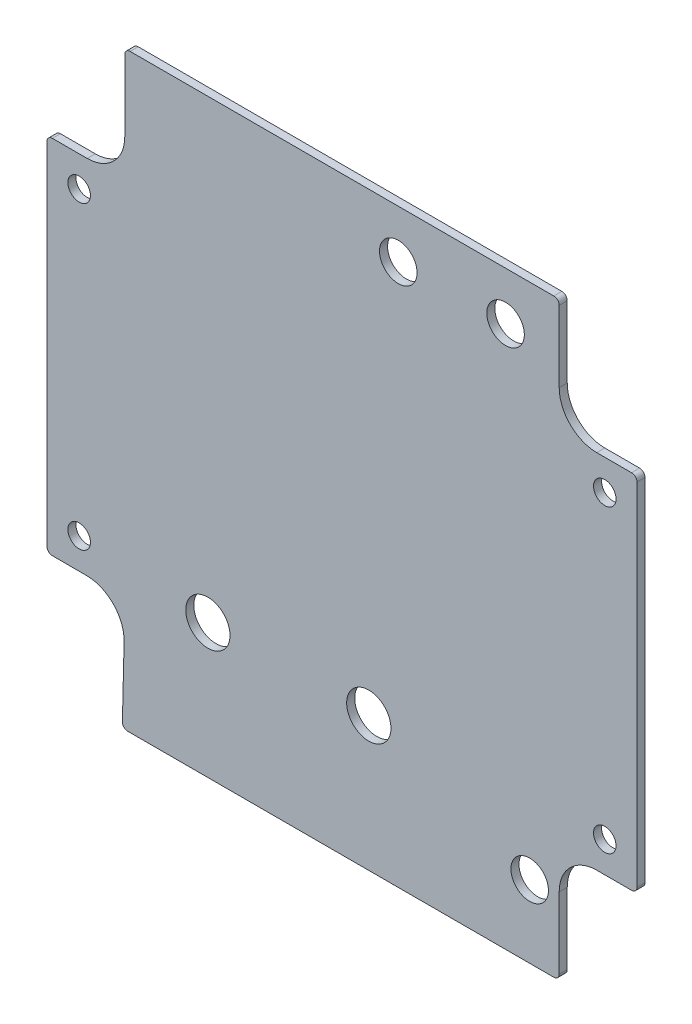
SolidWorks part; units mm, degrees
ref_plane "前基準面" through (0, 0, 0) normal (0, 0, 1) x (1, 0, 0)
ref_plane "上基準面" through (0, 0, 0) normal (0, 1, 0) x (1, 0, 0)
ref_plane "右基準面" through (0, 0, 0) normal (1, 0, 0) x (0, 0, -1)
sketch "草圖1" plane through (0, 0, 0) normal (0, 0, 1) x (1, 0, 0)
  line L27 (9.5192, -18.9462) -> (9.5192, -5.6591)
  line L28 (8.5192, -4.6591) -> (-70.4808, -4.6591)
  line L29 (-71.4808, -5.6591) -> (-71.4808, -18.9462)
  line L30 (-78.4808, -25.9462) -> (-84.9808, -25.9462)
  line L31 (-85.9808, -26.9462) -> (-85.9808, -92.3419)
  line L32 (-84.9834, -93.3419) -> (-78.5836, -93.3586)
  line L33 (-71.6039, -100.5265) -> (-71.9185, -113.6351)
  line L34 (-70.9188, -114.6591) -> (8.5192, -114.6591)
  line L35 (9.5192, -113.6591) -> (9.5192, -100.372)
  line L36 (16.5192, -93.372) -> (23.0192, -93.372)
  line L37 (24.0192, -92.372) -> (24.0192, -26.9462)
  line L38 (23.0192, -25.9462) -> (16.5192, -25.9462)
  line L39 (9.5192, -18.9462) -> (9.5192, -5.6591)
  line L40 (8.5192, -4.6591) -> (-70.4808, -4.6591)
  line L41 (-71.4808, -5.6591) -> (-71.4808, -18.9462)
  line L42 (-78.4808, -25.9462) -> (-84.9808, -25.9462)
  line L43 (-85.9808, -26.9462) -> (-85.9808, -92.3419)
  line L44 (-84.9834, -93.3419) -> (-78.5836, -93.3586)
  line L45 (-71.6039, -100.5265) -> (-71.9185, -113.6351)
  line L46 (-70.9188, -114.6591) -> (8.5192, -114.6591)
  line L47 (9.5192, -113.6591) -> (9.5192, -100.372)
  line L48 (16.5192, -93.372) -> (23.0192, -93.372)
  line L49 (24.0192, -92.372) -> (24.0192, -26.9462)
  line L50 (23.0192, -25.9462) -> (16.5192, -25.9462)
  arc A24 (9.5192, -18.9462) -> (16.5192, -25.9462) centre (16.5192, -18.9462) ccw
  arc A25 (9.5192, -5.6591) -> (8.5192, -4.6591) centre (8.5192, -5.6591) ccw
  arc A26 (-70.4808, -4.6591) -> (-71.4808, -5.6591) centre (-70.4808, -5.6591) ccw
  arc A27 (-78.4808, -25.9462) -> (-71.4808, -18.9462) centre (-78.4808, -18.9462) ccw
  arc A28 (-84.9808, -25.9462) -> (-85.9808, -26.9462) centre (-84.9808, -26.9462) ccw
  arc A29 (-85.9808, -92.3419) -> (-84.9834, -93.3419) centre (-84.9808, -92.3419) ccw
  arc A30 (-71.6039, -100.5265) -> (-78.5836, -93.3586) centre (-78.6019, -100.3586) ccw
  arc A31 (-71.9185, -113.6351) -> (-70.9188, -114.6591) centre (-70.9188, -113.6591) ccw
  arc A32 (8.5192, -114.6591) -> (9.5192, -113.6591) centre (8.5192, -113.6591) ccw
  arc A33 (16.5192, -93.372) -> (9.5192, -100.372) centre (16.5192, -100.372) ccw
  arc A34 (23.0192, -93.372) -> (24.0192, -92.372) centre (23.0192, -92.372) ccw
  arc A35 (24.0192, -26.9462) -> (23.0192, -25.9462) centre (23.0192, -26.9462) ccw
  arc A36 (9.5192, -18.9462) -> (16.5192, -25.9462) centre (16.5192, -18.9462) ccw
  arc A37 (9.5192, -5.6591) -> (8.5192, -4.6591) centre (8.5192, -5.6591) ccw
  arc A38 (-70.4808, -4.6591) -> (-71.4808, -5.6591) centre (-70.4808, -5.6591) ccw
  arc A39 (-78.4808, -25.9462) -> (-71.4808, -18.9462) centre (-78.4808, -18.9462) ccw
  arc A40 (-84.9808, -25.9462) -> (-85.9808, -26.9462) centre (-84.9808, -26.9462) ccw
  arc A41 (-85.9808, -92.3419) -> (-84.9834, -93.3419) centre (-84.9808, -92.3419) ccw
  arc A42 (-71.6039, -100.5265) -> (-78.5836, -93.3586) centre (-78.6019, -100.3586) ccw
  arc A43 (-71.9185, -113.6351) -> (-70.9188, -114.6591) centre (-70.9188, -113.6591) ccw
  arc A44 (8.5192, -114.6591) -> (9.5192, -113.6591) centre (8.5192, -113.6591) ccw
  arc A45 (16.5192, -93.372) -> (9.5192, -100.372) centre (16.5192, -100.372) ccw
  arc A46 (23.0192, -93.372) -> (24.0192, -92.372) centre (23.0192, -92.372) ccw
  arc A47 (24.0192, -26.9462) -> (23.0192, -25.9462) centre (23.0192, -26.9462) ccw
  dimension "D2" = 2
extrude "填料-伸長1" add sketch "草圖1" along normal blind 1.5
hole_wizard "M4 螺旋的螺孔鑽1" positions "草圖4" profile "草圖3" hole size "M4x0.7" standard "Ansi Metric" end condition through all
sketch "草圖4" plane through (0, 0, 0) normal (0, 0, -1) x (-1, 0, 0)
  point P0 (79.9808, -87.644)
  point P3 (-18.0192, -87.644)
  point P6 (-18.0192, -31.644)
  point P9 (79.9808, -31.644)
sketch "草圖3" plane through (-79.9808, -87.644, 0) normal (1, 0, 0) x (0, 1, 0)
  line L0 (0, 0) -> (0, 1.5)
  line L1 (0, 1.5) -> (2.1, 1.5)
  line L2 (2.1, 1.5) -> (2.1, 0)
  line L5 (2.1, 0) -> (0, 0)
  line L11 (0, -6.35) -> (0, 107.95) construction
  dimension "貫穿孔直徑" = 4.2
  dimension "貫穿孔深度" = 1.5
hole_wizard "M8 螺旋的螺孔鑽1" positions "草圖5" profile "草圖6" hole size "M8x1.0" standard "Ansi Metric" end condition through all
sketch "草圖5" plane through (0, 0, 1.5) normal (0, 0, 1) x (1, 0, 0)
  line L0 (-70.9188, -114.6591) -> (8.5192, -114.6591) construction
  line L1 (-85.9808, -26.9462) -> (-85.9808, -92.3419) construction
  point P0 (-55.9808, -89.6591)
  point P3 (-25.9808, -89.6591)
  dimension "D1" = 25
  dimension "D2" = 30
sketch "草圖6" plane through (-55.9808, -89.6591, 1.5) normal (1, 0, 0) x (0, -1, 0)
  line L0 (0, 0) -> (0, 1.5)
  line L1 (0, 1.5) -> (4.125, 1.5)
  line L2 (4.125, 1.5) -> (4.125, 0)
  line L5 (4.125, 0) -> (0, 0)
  line L11 (0, -6.35) -> (0, 107.95) construction
  dimension "貫穿孔直徑" = 8.25
  dimension "貫穿孔深度" = 1.5
sketch "草圖8" plane through (0, 0, 1.5) normal (0, 0, 1) x (1, 0, 0)
  line L0 (9.5192, -113.6591) -> (9.5192, -100.372) construction
  line L1 (-70.9188, -114.6591) -> (8.5192, -114.6591) construction
  circle A0 centre (4.0192, -101.1591) radius 3.5
  dimension "D1" = 7
  dimension "D2" = 5.5
  dimension "D3" = 13.5
extrude "除料-伸長1" cut sketch "草圖8" against normal through all
sketch "草圖9" plane through (0, 0, 1.5) normal (0, 0, 1) x (1, 0, 0)
  line L1 (8.5192, -4.6591) -> (-70.4808, -4.6591) construction
  line L2 (9.5192, -18.9462) -> (9.5192, -5.6591) construction
  circle A0 centre (-0.4808, -13.6591) radius 3.5
  circle A1 centre (-20.4808, -13.6591) radius 3.5
  dimension "D1" = 7
  dimension "D2" = 7
  dimension "D3" = 9
  dimension "D4" = 9
  dimension "D6" = 20
  dimension "D5" = 10
extrude "除料-伸長2" cut sketch "草圖9" against normal through all
